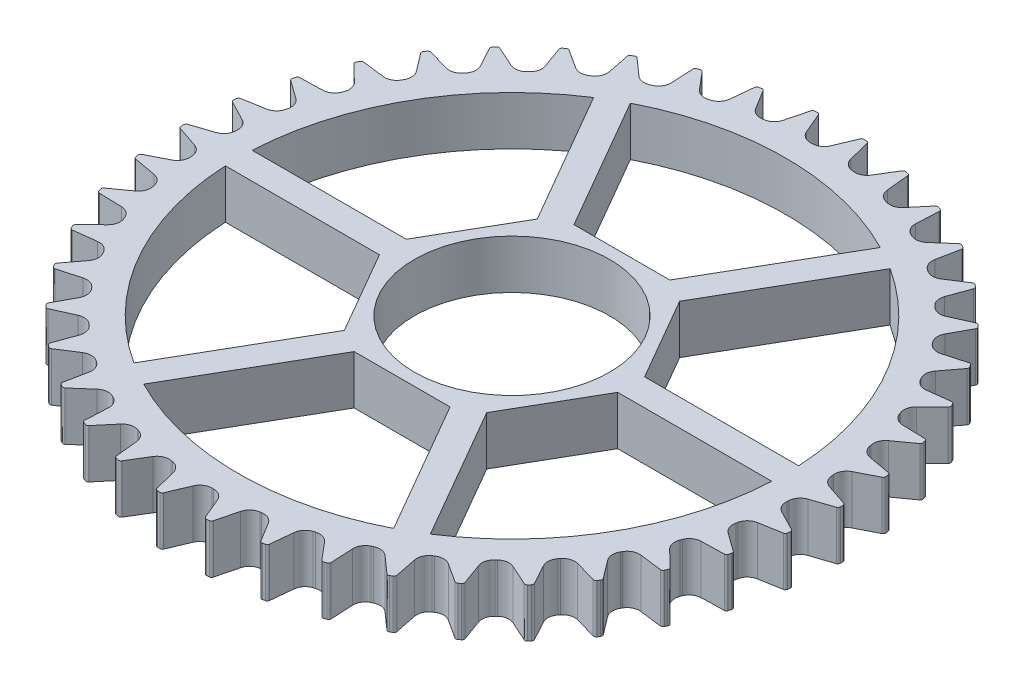
SolidWorks part; units mm, degrees
ref_plane "前视基准面" through (0, 0, 0) normal (0, 0, 1) x (1, 0, 0)
ref_plane "上视基准面" through (0, 0, 0) normal (0, 1, 0) x (1, 0, 0)
ref_plane "右视基准面" through (0, 0, 0) normal (1, 0, 0) x (0, 0, -1)
other "Configuration Table"
sketch "草图1" plane through (0, 0, 0) normal (0, 1, 0) x (1, 0, 0)
  line L0 (0, 0) -> (7.9279, 0) construction
  line L1 (0, 0) -> (0, 4.4256) construction
  line L2 (12.5574, 0.4423) -> (13.4318, 0.1478)
  line L3 (12.5574, -0.4423) -> (13.4318, -0.1478)
  line L4 (12.3513, -2.3089) -> (13.2598, -2.148)
  line L5 (12.4831, -1.4342) -> (13.3038, -1.8558)
  line L6 (11.8692, -4.124) -> (12.7915, -4.1003)
  line L7 (12.1299, -3.2787) -> (12.8786, -3.8179)
  line L8 (11.122, -5.847) -> (12.0375, -5.961)
  line L9 (11.5058, -5.05) -> (12.1658, -5.6947)
  line L10 (10.1263, -7.4393) -> (11.0146, -7.6885)
  line L11 (10.6246, -6.7084) -> (11.1811, -7.4443)
  line L12 (8.9044, -8.8654) -> (9.7457, -9.2443)
  line L13 (9.5061, -8.217) -> (9.9467, -9.0276)
  line L14 (7.4836, -10.0936) -> (8.2591, -10.5936)
  line L15 (8.1752, -9.542) -> (8.4901, -10.4093)
  line L16 (5.8957, -11.0962) -> (6.5879, -11.7062)
  line L17 (6.6618, -10.6539) -> (6.8439, -11.5584)
  line L18 (4.176, -11.851) -> (4.7696, -12.5573)
  line L19 (4.9995, -11.5278) -> (5.0447, -12.4493)
  line L20 (2.3631, -12.341) -> (2.8448, -13.1279)
  line L21 (3.2255, -12.1442) -> (3.1329, -13.0622)
  line L22 (0.4974, -12.5554) -> (0.8564, -13.4053)
  line L23 (1.3795, -12.4893) -> (1.1511, -13.3832)
  line L24 (-1.3795, -12.4893) -> (-1.1511, -13.3832)
  line L25 (-0.4974, -12.5554) -> (-0.8564, -13.4053)
  line L26 (-3.2255, -12.1442) -> (-3.1329, -13.0622)
  line L27 (-2.3631, -12.341) -> (-2.8448, -13.1279)
  line L28 (-4.9995, -11.5278) -> (-5.0447, -12.4493)
  line L29 (-4.176, -11.851) -> (-4.7696, -12.5573)
  line L30 (-6.6618, -10.6539) -> (-6.8439, -11.5584)
  line L31 (-5.8957, -11.0962) -> (-6.5879, -11.7062)
  line L32 (-8.1752, -9.542) -> (-8.4901, -10.4093)
  line L33 (-7.4836, -10.0936) -> (-8.2591, -10.5936)
  line L34 (-9.5061, -8.217) -> (-9.9467, -9.0276)
  line L35 (-8.9044, -8.8654) -> (-9.7457, -9.2443)
  line L36 (-10.6246, -6.7084) -> (-11.1811, -7.4443)
  line L37 (-10.1263, -7.4393) -> (-11.0146, -7.6885)
  line L38 (-11.5058, -5.05) -> (-12.1658, -5.6947)
  line L39 (-11.122, -5.847) -> (-12.0375, -5.961)
  line L40 (-12.1299, -3.2787) -> (-12.8786, -3.8179)
  line L41 (-11.8692, -4.124) -> (-12.7915, -4.1003)
  line L42 (-12.4831, -1.4342) -> (-13.3038, -1.8558)
  line L43 (-12.3513, -2.3089) -> (-13.2598, -2.148)
  line L44 (-12.5574, 0.4423) -> (-13.4318, 0.1478)
  line L45 (-12.5574, -0.4423) -> (-13.4318, -0.1478)
  line L46 (-12.3513, 2.3089) -> (-13.2598, 2.148)
  line L47 (-12.4831, 1.4342) -> (-13.3038, 1.8558)
  line L48 (-11.8692, 4.124) -> (-12.7915, 4.1003)
  line L49 (-12.1299, 3.2787) -> (-12.8786, 3.8179)
  line L50 (-11.122, 5.847) -> (-12.0375, 5.961)
  line L51 (-11.5058, 5.05) -> (-12.1658, 5.6947)
  line L52 (-10.1263, 7.4393) -> (-11.0146, 7.6885)
  line L53 (-10.6246, 6.7084) -> (-11.1811, 7.4443)
  line L54 (-8.9044, 8.8654) -> (-9.7457, 9.2443)
  line L55 (-9.5061, 8.217) -> (-9.9467, 9.0276)
  line L56 (-7.4836, 10.0936) -> (-8.2591, 10.5936)
  line L57 (-8.1752, 9.542) -> (-8.4901, 10.4093)
  line L58 (-5.8957, 11.0962) -> (-6.5879, 11.7062)
  line L59 (-6.6618, 10.6539) -> (-6.8439, 11.5584)
  line L60 (-4.176, 11.851) -> (-4.7696, 12.5573)
  line L61 (-4.9995, 11.5278) -> (-5.0447, 12.4493)
  line L62 (-2.3631, 12.341) -> (-2.8448, 13.1279)
  line L63 (-3.2255, 12.1442) -> (-3.1329, 13.0622)
  line L64 (-0.4974, 12.5554) -> (-0.8564, 13.4053)
  line L65 (-1.3795, 12.4893) -> (-1.1511, 13.3832)
  line L66 (1.3795, 12.4893) -> (1.1511, 13.3832)
  line L67 (0.4974, 12.5554) -> (0.8564, 13.4053)
  line L68 (3.2255, 12.1442) -> (3.1329, 13.0622)
  line L69 (2.3631, 12.341) -> (2.8448, 13.1279)
  line L70 (4.9995, 11.5278) -> (5.0447, 12.4493)
  line L71 (4.176, 11.851) -> (4.7696, 12.5573)
  line L72 (6.6618, 10.6539) -> (6.8439, 11.5584)
  line L73 (5.8957, 11.0962) -> (6.5879, 11.7062)
  line L74 (8.1752, 9.542) -> (8.4901, 10.4093)
  line L75 (7.4836, 10.0936) -> (8.2591, 10.5936)
  line L76 (9.5061, 8.217) -> (9.9467, 9.0276)
  line L77 (8.9044, 8.8654) -> (9.7457, 9.2443)
  line L78 (10.6246, 6.7084) -> (11.1811, 7.4443)
  line L79 (10.1263, 7.4393) -> (11.0146, 7.6885)
  line L80 (11.5058, 5.05) -> (12.1658, 5.6947)
  line L81 (11.122, 5.847) -> (12.0375, 5.961)
  line L82 (12.1299, 3.2787) -> (12.8786, 3.8179)
  line L83 (11.8692, 4.124) -> (12.7915, 4.1003)
  line L84 (12.4831, 1.4342) -> (13.3038, 1.8558)
  line L85 (12.3513, 2.3089) -> (13.2598, 2.148)
  line L95 (2.5981, 4.5) -> (-2.5981, 4.5) construction
  line L96 (2.5981, 4.5) -> (4.8786, 0.55) construction
  line L97 (0, 0) -> (2.5981, 4.5) construction
  line L98 (-2.5981, 4.5) -> (-4.8786, 0.55) construction
  line L99 (2.9156, -3.95) -> (4.8786, -0.55)
  line L100 (1.963, -4.5) -> (-1.963, -4.5)
  line L101 (-2.9156, -3.95) -> (-4.8786, -0.55)
  line L102 (8.1752, 0) -> (11.2, 0) construction
  line L103 (4.8786, 0.55) -> (11.1865, 0.55)
  line L104 (4.8786, -0.55) -> (11.1865, -0.55)
  line L105 (2.9156, -3.95) -> (6.0696, -9.4128)
  line L106 (1.963, -4.5) -> (5.1169, -9.9628)
  line L107 (-1.963, -4.5) -> (-5.1169, -9.9628)
  line L108 (-2.9156, -3.95) -> (-6.0696, -9.4128)
  line L109 (-4.8786, -0.55) -> (-11.1865, -0.55)
  line L110 (-4.8786, 0.55) -> (-11.1865, 0.55)
  line L111 (-2.9156, 3.95) -> (-6.0696, 9.4128)
  line L112 (-1.963, 4.5) -> (-5.1169, 9.9628)
  line L113 (1.963, 4.5) -> (5.1169, 9.9628)
  line L114 (2.9156, 3.95) -> (6.0696, 9.4128)
  line L115 (0, 0) -> (12.1829, 1.2805) construction
  line L116 (12.1829, -1.2805) -> (0, 0) construction
  line L117 (-4.8786, 0.55) -> (-2.9156, 3.95)
  line L118 (-1.963, 4.5) -> (1.963, 4.5)
  line L119 (2.9156, 3.95) -> (4.8786, 0.55)
  circle A0 centre (0, 0) radius 11.2 construction
  circle A1 centre (0, 0) radius 12.25 construction
  circle A2 centre (0, 0) radius 13.5 construction
  arc A3 (13.4999, 0.0534) -> (13.4999, -0.0534) centre (0, 0) cw
  arc A4 (12.2183, 0.8802) -> (12.1829, 1.2805) centre (0, 0) ccw construction
  arc A5 (13.4318, -0.1478) -> (13.4999, -0.0534) centre (13.3999, -0.053) ccw
  arc A6 (13.4318, 0.1478) -> (13.4999, 0.0534) centre (13.3999, 0.053) cw
  arc A7 (12.2183, -0.8802) -> (12.1829, -1.2805) centre (0, 0) cw construction
  arc A8 (12.5574, -0.4423) -> (12.2183, -0.8802) centre (12.717, -0.9161) ccw
  arc A9 (12.5574, 0.4423) -> (12.2183, 0.8802) centre (12.717, 0.9161) cw
  arc A10 (12.3513, -2.3089) -> (11.9507, -2.6914) centre (12.4385, -2.8013) ccw
  arc A11 (12.4831, -1.4342) -> (12.2131, -0.9507) centre (12.7115, -0.9895) cw
  arc A12 (13.3038, -1.8558) -> (13.3571, -1.9593) centre (13.2581, -1.9447) cw
  arc A13 (13.3571, -1.9593) -> (13.3412, -2.0649) centre (0, 0) cw
  arc A14 (13.2598, -2.148) -> (13.3412, -2.0649) centre (13.2423, -2.0496) ccw
  arc A15 (11.8692, -4.124) -> (11.4161, -4.4425) centre (11.882, -4.6238) ccw
  arc A16 (12.1299, -3.2787) -> (11.935, -2.7603) centre (12.4221, -2.873) cw
  arc A17 (12.8786, -3.8179) -> (12.9159, -3.9281) centre (12.8202, -3.899) cw
  arc A18 (12.9159, -3.9281) -> (12.8844, -4.0302) centre (0, 0) cw
  arc A19 (12.7915, -4.1003) -> (12.8844, -4.0302) centre (12.789, -4.0003) ccw
  arc A20 (11.122, -5.847) -> (10.6264, -6.0944) centre (11.0602, -6.3431) ccw
  arc A21 (11.5058, -5.05) -> (11.3902, -4.5083) centre (11.8552, -4.6923) cw
  arc A22 (12.1658, -5.6947) -> (12.1862, -5.8093) centre (12.0959, -5.7662) cw
  arc A23 (12.1862, -5.8093) -> (12.1398, -5.9055) centre (0, 0) cw
  arc A24 (12.0375, -5.961) -> (12.1398, -5.9055) centre (12.0499, -5.8618) ccw
  arc A25 (10.1263, -7.4393) -> (9.5994, -7.6101) centre (9.9912, -7.9207) ccw
  arc A26 (10.6246, -6.7084) -> (10.5911, -6.1556) centre (11.0234, -6.4068) cw
  arc A27 (11.1811, -7.4443) -> (11.1842, -7.5606) centre (11.1014, -7.5046) cw
  arc A28 (11.1842, -7.5606) -> (11.1241, -7.6489) centre (0, 0) cw
  arc A29 (11.0146, -7.6885) -> (11.1241, -7.6489) centre (11.0417, -7.5922) ccw
  arc A30 (8.9044, -8.8654) -> (8.358, -8.9558) centre (8.6991, -9.3214) ccw
  arc A31 (9.5061, -8.217) -> (9.5554, -7.6653) centre (9.9454, -7.9782) cw
  arc A32 (9.9467, -9.0276) -> (9.9324, -9.1431) centre (9.8589, -9.0754) cw
  arc A33 (9.9324, -9.1431) -> (9.8598, -9.2214) centre (0, 0) cw
  arc A34 (9.7457, -9.2443) -> (9.8598, -9.2214) centre (9.7868, -9.1531) ccw
  arc A35 (7.4836, -10.0936) -> (6.9298, -10.1015) centre (7.2127, -10.5138) ccw
  arc A36 (8.1752, -9.542) -> (8.3062, -9.0039) centre (8.6452, -9.3714) cw
  arc A37 (8.4901, -10.4093) -> (8.4588, -10.5213) centre (8.3961, -10.4434) cw
  arc A38 (8.4588, -10.5213) -> (8.3753, -10.5879) centre (0, 0) cw
  arc A39 (8.2591, -10.5936) -> (8.3753, -10.5879) centre (8.3133, -10.5095) ccw
  arc A40 (5.8957, -11.0962) -> (5.3469, -11.0215) centre (5.5651, -11.4713) ccw
  arc A41 (6.6618, -10.6539) -> (6.8714, -10.1413) centre (7.1519, -10.5552) cw
  arc A42 (6.8439, -11.5584) -> (6.7962, -11.6646) centre (6.7458, -11.5781) cw
  arc A43 (6.7962, -11.6646) -> (6.7037, -11.718) centre (0, 0) cw
  arc A44 (6.5879, -11.7062) -> (6.7037, -11.718) centre (6.654, -11.6312) ccw
  arc A45 (4.176, -11.851) -> (3.6445, -11.6953) centre (3.7933, -12.1727) ccw
  arc A46 (4.9995, -11.5278) -> (5.2832, -11.0522) centre (5.4989, -11.5033) cw
  arc A47 (5.0447, -12.4493) -> (4.9818, -12.5472) centre (4.9449, -12.4542) cw
  arc A48 (4.9818, -12.5472) -> (4.8824, -12.5862) centre (0, 0) cw
  arc A49 (4.7696, -12.5573) -> (4.8824, -12.5862) centre (4.8462, -12.493) ccw
  arc A50 (2.3631, -12.341) -> (1.8607, -12.1079) centre (1.9367, -12.6021) ccw
  arc A51 (3.2255, -12.1442) -> (3.577, -11.7161) centre (3.723, -12.1943) cw
  arc A52 (3.1329, -13.0622) -> (3.0561, -13.1495) centre (3.0334, -13.0521) cw
  arc A53 (3.0561, -13.1495) -> (2.9519, -13.1733) centre (0, 0) cw
  arc A54 (2.8448, -13.1279) -> (2.9519, -13.1733) centre (2.9301, -13.0757) ccw
  arc A55 (0.4974, -12.5554) -> (0.0353, -12.2499) centre (0.0368, -12.7499) ccw
  arc A56 (1.3795, -12.4893) -> (1.7908, -12.1184) centre (1.8639, -12.613) cw
  arc A57 (1.1511, -13.3832) -> (1.0621, -13.4582) centre (1.0542, -13.3585) cw
  arc A58 (1.0621, -13.4582) -> (0.9556, -13.4661) centre (0, 0) cw
  arc A59 (0.8564, -13.4053) -> (0.9556, -13.4661) centre (0.9485, -13.3664) ccw
  arc A60 (-1.3795, -12.4893) -> (-1.7908, -12.1184) centre (-1.8639, -12.613) ccw
  arc A61 (-0.4974, -12.5554) -> (-0.0353, -12.2499) centre (-0.0368, -12.7499) cw
  arc A62 (-0.8564, -13.4053) -> (-0.9556, -13.4661) centre (-0.9485, -13.3664) cw
  arc A63 (-0.9556, -13.4661) -> (-1.0621, -13.4582) centre (0, 0) cw
  arc A64 (-1.1511, -13.3832) -> (-1.0621, -13.4582) centre (-1.0542, -13.3585) ccw
  arc A65 (-3.2255, -12.1442) -> (-3.577, -11.7161) centre (-3.723, -12.1943) ccw
  arc A66 (-2.3631, -12.341) -> (-1.8607, -12.1079) centre (-1.9367, -12.6021) cw
  arc A67 (-2.8448, -13.1279) -> (-2.9519, -13.1733) centre (-2.9301, -13.0757) cw
  arc A68 (-2.9519, -13.1733) -> (-3.0561, -13.1495) centre (0, 0) cw
  arc A69 (-3.1329, -13.0622) -> (-3.0561, -13.1495) centre (-3.0334, -13.0521) ccw
  arc A70 (-4.9995, -11.5278) -> (-5.2832, -11.0522) centre (-5.4989, -11.5033) ccw
  arc A71 (-4.176, -11.851) -> (-3.6445, -11.6953) centre (-3.7933, -12.1727) cw
  arc A72 (-4.7696, -12.5573) -> (-4.8824, -12.5862) centre (-4.8462, -12.493) cw
  arc A73 (-4.8824, -12.5862) -> (-4.9818, -12.5472) centre (0, 0) cw
  arc A74 (-5.0447, -12.4493) -> (-4.9818, -12.5472) centre (-4.9449, -12.4542) ccw
  arc A75 (-6.6618, -10.6539) -> (-6.8714, -10.1413) centre (-7.1519, -10.5552) ccw
  arc A76 (-5.8957, -11.0962) -> (-5.3469, -11.0215) centre (-5.5651, -11.4713) cw
  arc A77 (-6.5879, -11.7062) -> (-6.7037, -11.718) centre (-6.654, -11.6312) cw
  arc A78 (-6.7037, -11.718) -> (-6.7962, -11.6646) centre (0, 0) cw
  arc A79 (-6.8439, -11.5584) -> (-6.7962, -11.6646) centre (-6.7458, -11.5781) ccw
  arc A80 (-8.1752, -9.542) -> (-8.3062, -9.0039) centre (-8.6452, -9.3714) ccw
  arc A81 (-7.4836, -10.0936) -> (-6.9298, -10.1015) centre (-7.2127, -10.5138) cw
  arc A82 (-8.2591, -10.5936) -> (-8.3753, -10.5879) centre (-8.3133, -10.5095) cw
  arc A83 (-8.3753, -10.5879) -> (-8.4588, -10.5213) centre (0, 0) cw
  arc A84 (-8.4901, -10.4093) -> (-8.4588, -10.5213) centre (-8.3961, -10.4434) ccw
  arc A85 (-9.5061, -8.217) -> (-9.5554, -7.6653) centre (-9.9454, -7.9782) ccw
  arc A86 (-8.9044, -8.8654) -> (-8.358, -8.9558) centre (-8.6991, -9.3214) cw
  arc A87 (-9.7457, -9.2443) -> (-9.8598, -9.2214) centre (-9.7868, -9.1531) cw
  arc A88 (-9.8598, -9.2214) -> (-9.9324, -9.1431) centre (0, 0) cw
  arc A89 (-9.9467, -9.0276) -> (-9.9324, -9.1431) centre (-9.8589, -9.0754) ccw
  arc A90 (-10.6246, -6.7084) -> (-10.5911, -6.1556) centre (-11.0234, -6.4068) ccw
  arc A91 (-10.1263, -7.4393) -> (-9.5994, -7.6101) centre (-9.9912, -7.9207) cw
  arc A92 (-11.0146, -7.6885) -> (-11.1241, -7.6489) centre (-11.0417, -7.5922) cw
  arc A93 (-11.1241, -7.6489) -> (-11.1842, -7.5606) centre (0, 0) cw
  arc A94 (-11.1811, -7.4443) -> (-11.1842, -7.5606) centre (-11.1014, -7.5046) ccw
  arc A95 (-11.5058, -5.05) -> (-11.3902, -4.5083) centre (-11.8552, -4.6923) ccw
  arc A96 (-11.122, -5.847) -> (-10.6264, -6.0944) centre (-11.0602, -6.3431) cw
  arc A97 (-12.0375, -5.961) -> (-12.1398, -5.9055) centre (-12.0499, -5.8618) cw
  arc A98 (-12.1398, -5.9055) -> (-12.1862, -5.8093) centre (0, 0) cw
  arc A99 (-12.1658, -5.6947) -> (-12.1862, -5.8093) centre (-12.0959, -5.7662) ccw
  arc A100 (-12.1299, -3.2787) -> (-11.935, -2.7603) centre (-12.4221, -2.873) ccw
  arc A101 (-11.8692, -4.124) -> (-11.4161, -4.4425) centre (-11.882, -4.6238) cw
  arc A102 (-12.7915, -4.1003) -> (-12.8844, -4.0302) centre (-12.789, -4.0003) cw
  arc A103 (-12.8844, -4.0302) -> (-12.9159, -3.9281) centre (0, 0) cw
  arc A104 (-12.8786, -3.8179) -> (-12.9159, -3.9281) centre (-12.8202, -3.899) ccw
  arc A105 (-12.4831, -1.4342) -> (-12.2131, -0.9507) centre (-12.7115, -0.9895) ccw
  arc A106 (-12.3513, -2.3089) -> (-11.9507, -2.6914) centre (-12.4385, -2.8013) cw
  arc A107 (-13.2598, -2.148) -> (-13.3412, -2.0649) centre (-13.2423, -2.0496) cw
  arc A108 (-13.3412, -2.0649) -> (-13.3571, -1.9593) centre (0, 0) cw
  arc A109 (-13.3038, -1.8558) -> (-13.3571, -1.9593) centre (-13.2581, -1.9447) ccw
  arc A110 (-12.5574, 0.4423) -> (-12.2183, 0.8802) centre (-12.717, 0.9161) ccw
  arc A111 (-12.5574, -0.4423) -> (-12.2183, -0.8802) centre (-12.717, -0.9161) cw
  arc A112 (-13.4318, -0.1478) -> (-13.4999, -0.0534) centre (-13.3999, -0.053) cw
  arc A113 (-13.4999, -0.0534) -> (-13.4999, 0.0534) centre (0, 0) cw
  arc A114 (-13.4318, 0.1478) -> (-13.4999, 0.0534) centre (-13.3999, 0.053) ccw
  arc A115 (-12.3513, 2.3089) -> (-11.9507, 2.6914) centre (-12.4385, 2.8013) ccw
  arc A116 (-12.4831, 1.4342) -> (-12.2131, 0.9507) centre (-12.7115, 0.9895) cw
  arc A117 (-13.3038, 1.8558) -> (-13.3571, 1.9593) centre (-13.2581, 1.9447) cw
  arc A118 (-13.3571, 1.9593) -> (-13.3412, 2.0649) centre (0, 0) cw
  arc A119 (-13.2598, 2.148) -> (-13.3412, 2.0649) centre (-13.2423, 2.0496) ccw
  arc A120 (-11.8692, 4.124) -> (-11.4161, 4.4425) centre (-11.882, 4.6238) ccw
  arc A121 (-12.1299, 3.2787) -> (-11.935, 2.7603) centre (-12.4221, 2.873) cw
  arc A122 (-12.8786, 3.8179) -> (-12.9159, 3.9281) centre (-12.8202, 3.899) cw
  arc A123 (-12.9159, 3.9281) -> (-12.8844, 4.0302) centre (0, 0) cw
  arc A124 (-12.7915, 4.1003) -> (-12.8844, 4.0302) centre (-12.789, 4.0003) ccw
  arc A125 (-11.122, 5.847) -> (-10.6264, 6.0944) centre (-11.0602, 6.3431) ccw
  arc A126 (-11.5058, 5.05) -> (-11.3902, 4.5083) centre (-11.8552, 4.6923) cw
  arc A127 (-12.1658, 5.6947) -> (-12.1862, 5.8093) centre (-12.0959, 5.7662) cw
  arc A128 (-12.1862, 5.8093) -> (-12.1398, 5.9055) centre (0, 0) cw
  arc A129 (-12.0375, 5.961) -> (-12.1398, 5.9055) centre (-12.0499, 5.8618) ccw
  arc A130 (-10.1263, 7.4393) -> (-9.5994, 7.6101) centre (-9.9912, 7.9207) ccw
  arc A131 (-10.6246, 6.7084) -> (-10.5911, 6.1556) centre (-11.0234, 6.4068) cw
  arc A132 (-11.1811, 7.4443) -> (-11.1842, 7.5606) centre (-11.1014, 7.5046) cw
  arc A133 (-11.1842, 7.5606) -> (-11.1241, 7.6489) centre (0, 0) cw
  arc A134 (-11.0146, 7.6885) -> (-11.1241, 7.6489) centre (-11.0417, 7.5922) ccw
  arc A135 (-8.9044, 8.8654) -> (-8.358, 8.9558) centre (-8.6991, 9.3214) ccw
  arc A136 (-9.5061, 8.217) -> (-9.5554, 7.6653) centre (-9.9454, 7.9782) cw
  arc A137 (-9.9467, 9.0276) -> (-9.9324, 9.1431) centre (-9.8589, 9.0754) cw
  arc A138 (-9.9324, 9.1431) -> (-9.8598, 9.2214) centre (0, 0) cw
  arc A139 (-9.7457, 9.2443) -> (-9.8598, 9.2214) centre (-9.7868, 9.1531) ccw
  arc A140 (-7.4836, 10.0936) -> (-6.9298, 10.1015) centre (-7.2127, 10.5138) ccw
  arc A141 (-8.1752, 9.542) -> (-8.3062, 9.0039) centre (-8.6452, 9.3714) cw
  arc A142 (-8.4901, 10.4093) -> (-8.4588, 10.5213) centre (-8.3961, 10.4434) cw
  arc A143 (-8.4588, 10.5213) -> (-8.3753, 10.5879) centre (0, 0) cw
  arc A144 (-8.2591, 10.5936) -> (-8.3753, 10.5879) centre (-8.3133, 10.5095) ccw
  arc A145 (-5.8957, 11.0962) -> (-5.3469, 11.0215) centre (-5.5651, 11.4713) ccw
  arc A146 (-6.6618, 10.6539) -> (-6.8714, 10.1413) centre (-7.1519, 10.5552) cw
  arc A147 (-6.8439, 11.5584) -> (-6.7962, 11.6646) centre (-6.7458, 11.5781) cw
  arc A148 (-6.7962, 11.6646) -> (-6.7037, 11.718) centre (0, 0) cw
  arc A149 (-6.5879, 11.7062) -> (-6.7037, 11.718) centre (-6.654, 11.6312) ccw
  arc A150 (-4.176, 11.851) -> (-3.6445, 11.6953) centre (-3.7933, 12.1727) ccw
  arc A151 (-4.9995, 11.5278) -> (-5.2832, 11.0522) centre (-5.4989, 11.5033) cw
  arc A152 (-5.0447, 12.4493) -> (-4.9818, 12.5472) centre (-4.9449, 12.4542) cw
  arc A153 (-4.9818, 12.5472) -> (-4.8824, 12.5862) centre (0, 0) cw
  arc A154 (-4.7696, 12.5573) -> (-4.8824, 12.5862) centre (-4.8462, 12.493) ccw
  arc A155 (-2.3631, 12.341) -> (-1.8607, 12.1079) centre (-1.9367, 12.6021) ccw
  arc A156 (-3.2255, 12.1442) -> (-3.577, 11.7161) centre (-3.723, 12.1943) cw
  arc A157 (-3.1329, 13.0622) -> (-3.0561, 13.1495) centre (-3.0334, 13.0521) cw
  arc A158 (-3.0561, 13.1495) -> (-2.9519, 13.1733) centre (0, 0) cw
  arc A159 (-2.8448, 13.1279) -> (-2.9519, 13.1733) centre (-2.9301, 13.0757) ccw
  arc A160 (-0.4974, 12.5554) -> (-0.0353, 12.2499) centre (-0.0368, 12.7499) ccw
  arc A161 (-1.3795, 12.4893) -> (-1.7908, 12.1184) centre (-1.8639, 12.613) cw
  arc A162 (-1.1511, 13.3832) -> (-1.0621, 13.4582) centre (-1.0542, 13.3585) cw
  arc A163 (-1.0621, 13.4582) -> (-0.9556, 13.4661) centre (0, 0) cw
  arc A164 (-0.8564, 13.4053) -> (-0.9556, 13.4661) centre (-0.9485, 13.3664) ccw
  arc A165 (1.3795, 12.4893) -> (1.7908, 12.1184) centre (1.8639, 12.613) ccw
  arc A166 (0.4974, 12.5554) -> (0.0353, 12.2499) centre (0.0368, 12.7499) cw
  arc A167 (0.8564, 13.4053) -> (0.9556, 13.4661) centre (0.9485, 13.3664) cw
  arc A168 (0.9556, 13.4661) -> (1.0621, 13.4582) centre (0, 0) cw
  arc A169 (1.1511, 13.3832) -> (1.0621, 13.4582) centre (1.0542, 13.3585) ccw
  arc A170 (3.2255, 12.1442) -> (3.577, 11.7161) centre (3.723, 12.1943) ccw
  arc A171 (2.3631, 12.341) -> (1.8607, 12.1079) centre (1.9367, 12.6021) cw
  arc A172 (2.8448, 13.1279) -> (2.9519, 13.1733) centre (2.9301, 13.0757) cw
  arc A173 (2.9519, 13.1733) -> (3.0561, 13.1495) centre (0, 0) cw
  arc A174 (3.1329, 13.0622) -> (3.0561, 13.1495) centre (3.0334, 13.0521) ccw
  arc A175 (4.9995, 11.5278) -> (5.2832, 11.0522) centre (5.4989, 11.5033) ccw
  arc A176 (4.176, 11.851) -> (3.6445, 11.6953) centre (3.7933, 12.1727) cw
  arc A177 (4.7696, 12.5573) -> (4.8824, 12.5862) centre (4.8462, 12.493) cw
  arc A178 (4.8824, 12.5862) -> (4.9818, 12.5472) centre (0, 0) cw
  arc A179 (5.0447, 12.4493) -> (4.9818, 12.5472) centre (4.9449, 12.4542) ccw
  arc A180 (6.6618, 10.6539) -> (6.8714, 10.1413) centre (7.1519, 10.5552) ccw
  arc A181 (5.8957, 11.0962) -> (5.3469, 11.0215) centre (5.5651, 11.4713) cw
  arc A182 (6.5879, 11.7062) -> (6.7037, 11.718) centre (6.654, 11.6312) cw
  arc A183 (6.7037, 11.718) -> (6.7962, 11.6646) centre (0, 0) cw
  arc A184 (6.8439, 11.5584) -> (6.7962, 11.6646) centre (6.7458, 11.5781) ccw
  arc A185 (8.1752, 9.542) -> (8.3062, 9.0039) centre (8.6452, 9.3714) ccw
  arc A186 (7.4836, 10.0936) -> (6.9298, 10.1015) centre (7.2127, 10.5138) cw
  arc A187 (8.2591, 10.5936) -> (8.3753, 10.5879) centre (8.3133, 10.5095) cw
  arc A188 (8.3753, 10.5879) -> (8.4588, 10.5213) centre (0, 0) cw
  arc A189 (8.4901, 10.4093) -> (8.4588, 10.5213) centre (8.3961, 10.4434) ccw
  arc A190 (9.5061, 8.217) -> (9.5554, 7.6653) centre (9.9454, 7.9782) ccw
  arc A191 (8.9044, 8.8654) -> (8.358, 8.9558) centre (8.6991, 9.3214) cw
  arc A192 (9.7457, 9.2443) -> (9.8598, 9.2214) centre (9.7868, 9.1531) cw
  arc A193 (9.8598, 9.2214) -> (9.9324, 9.1431) centre (0, 0) cw
  arc A194 (9.9467, 9.0276) -> (9.9324, 9.1431) centre (9.8589, 9.0754) ccw
  arc A195 (10.6246, 6.7084) -> (10.5911, 6.1556) centre (11.0234, 6.4068) ccw
  arc A196 (10.1263, 7.4393) -> (9.5994, 7.6101) centre (9.9912, 7.9207) cw
  arc A197 (11.0146, 7.6885) -> (11.1241, 7.6489) centre (11.0417, 7.5922) cw
  arc A198 (11.1241, 7.6489) -> (11.1842, 7.5606) centre (0, 0) cw
  arc A199 (11.1811, 7.4443) -> (11.1842, 7.5606) centre (11.1014, 7.5046) ccw
  arc A200 (11.5058, 5.05) -> (11.3902, 4.5083) centre (11.8552, 4.6923) ccw
  arc A201 (11.122, 5.847) -> (10.6264, 6.0944) centre (11.0602, 6.3431) cw
  arc A202 (12.0375, 5.961) -> (12.1398, 5.9055) centre (12.0499, 5.8618) cw
  arc A203 (12.1398, 5.9055) -> (12.1862, 5.8093) centre (0, 0) cw
  arc A204 (12.1658, 5.6947) -> (12.1862, 5.8093) centre (12.0959, 5.7662) ccw
  arc A205 (12.1299, 3.2787) -> (11.935, 2.7603) centre (12.4221, 2.873) ccw
  arc A206 (11.8692, 4.124) -> (11.4161, 4.4425) centre (11.882, 4.6238) cw
  arc A207 (12.7915, 4.1003) -> (12.8844, 4.0302) centre (12.789, 4.0003) cw
  arc A208 (12.8844, 4.0302) -> (12.9159, 3.9281) centre (0, 0) cw
  arc A209 (12.8786, 3.8179) -> (12.9159, 3.9281) centre (12.8202, 3.899) ccw
  arc A210 (12.4831, 1.4342) -> (12.2131, 0.9507) centre (12.7115, 0.9895) ccw
  arc A211 (12.3513, 2.3089) -> (11.9507, 2.6914) centre (12.4385, 2.8013) cw
  arc A212 (13.2598, 2.148) -> (13.3412, 2.0649) centre (13.2423, 2.0496) cw
  arc A213 (13.3412, 2.0649) -> (13.3571, 1.9593) centre (0, 0) cw
  arc A214 (13.3038, 1.8558) -> (13.3571, 1.9593) centre (13.2581, 1.9447) ccw
  circle A216 centre (0, 0) radius 4
  arc A217 (11.1865, 0.55) -> (6.0696, 9.4128) centre (0, 0) ccw
  arc A218 (5.1169, 9.9628) -> (-5.1169, 9.9628) centre (0, 0) ccw
  arc A219 (-6.0696, 9.4128) -> (-11.1865, 0.55) centre (0, 0) ccw
  arc A220 (-11.1865, -0.55) -> (-6.0696, -9.4128) centre (0, 0) ccw
  arc A221 (-5.1169, -9.9628) -> (5.1169, -9.9628) centre (0, 0) ccw
  arc A222 (6.0696, -9.4128) -> (11.1865, -0.55) centre (0, 0) ccw
  arc A223 (12.2131, 0.9507) -> (12.2183, 0.8802) centre (0, 0) cw
  arc A224 (12.2183, -0.8802) -> (12.2131, -0.9507) centre (0, 0) cw
  arc A225 (11.9507, -2.6914) -> (11.935, -2.7603) centre (0, 0) cw
  arc A226 (11.4161, -4.4425) -> (11.3902, -4.5083) centre (0, 0) cw
  arc A227 (10.6264, -6.0944) -> (10.5911, -6.1556) centre (0, 0) cw
  arc A228 (9.5994, -7.6101) -> (9.5554, -7.6653) centre (0, 0) cw
  arc A229 (8.358, -8.9558) -> (8.3062, -9.0039) centre (0, 0) cw
  arc A230 (6.9298, -10.1015) -> (6.8714, -10.1413) centre (0, 0) cw
  arc A231 (5.3469, -11.0215) -> (5.2832, -11.0522) centre (0, 0) cw
  arc A232 (3.6445, -11.6953) -> (3.577, -11.7161) centre (0, 0) cw
  arc A233 (1.8607, -12.1079) -> (1.7908, -12.1184) centre (0, 0) cw
  arc A234 (0.0353, -12.2499) -> (-0.0353, -12.2499) centre (0, 0) cw
  arc A235 (-1.7908, -12.1184) -> (-1.8607, -12.1079) centre (0, 0) cw
  arc A236 (-3.577, -11.7161) -> (-3.6445, -11.6953) centre (0, 0) cw
  arc A237 (-5.2832, -11.0522) -> (-5.3469, -11.0215) centre (0, 0) cw
  arc A238 (-6.8714, -10.1413) -> (-6.9298, -10.1015) centre (0, 0) cw
  arc A239 (-8.3062, -9.0039) -> (-8.358, -8.9558) centre (0, 0) cw
  arc A240 (-9.5554, -7.6653) -> (-9.5994, -7.6101) centre (0, 0) cw
  arc A241 (-10.5911, -6.1556) -> (-10.6264, -6.0944) centre (0, 0) cw
  arc A242 (-11.3902, -4.5083) -> (-11.4161, -4.4425) centre (0, 0) cw
  arc A243 (-11.935, -2.7603) -> (-11.9507, -2.6914) centre (0, 0) cw
  arc A244 (-12.2131, -0.9507) -> (-12.2183, -0.8802) centre (0, 0) cw
  arc A245 (-12.2183, 0.8802) -> (-12.2131, 0.9507) centre (0, 0) cw
  arc A246 (-11.9507, 2.6914) -> (-11.935, 2.7603) centre (0, 0) cw
  arc A247 (-11.4161, 4.4425) -> (-11.3902, 4.5083) centre (0, 0) cw
  arc A248 (-10.6264, 6.0944) -> (-10.5911, 6.1556) centre (0, 0) cw
  arc A249 (-9.5994, 7.6101) -> (-9.5554, 7.6653) centre (0, 0) cw
  arc A250 (-8.358, 8.9558) -> (-8.3062, 9.0039) centre (0, 0) cw
  arc A251 (-6.9298, 10.1015) -> (-6.8714, 10.1413) centre (0, 0) cw
  arc A252 (-5.3469, 11.0215) -> (-5.2832, 11.0522) centre (0, 0) cw
  arc A253 (-3.6445, 11.6953) -> (-3.577, 11.7161) centre (0, 0) cw
  arc A254 (-1.8607, 12.1079) -> (-1.7908, 12.1184) centre (0, 0) cw
  arc A255 (-0.0353, 12.2499) -> (0.0353, 12.2499) centre (0, 0) cw
  arc A256 (1.7908, 12.1184) -> (1.8607, 12.1079) centre (0, 0) cw
  arc A257 (3.577, 11.7161) -> (3.6445, 11.6953) centre (0, 0) cw
  arc A258 (5.2832, 11.0522) -> (5.3469, 11.0215) centre (0, 0) cw
  arc A259 (6.8714, 10.1413) -> (6.9298, 10.1015) centre (0, 0) cw
  arc A260 (8.3062, 9.0039) -> (8.358, 8.9558) centre (0, 0) cw
  arc A261 (9.5554, 7.6653) -> (9.5994, 7.6101) centre (0, 0) cw
  arc A262 (10.5911, 6.1556) -> (10.6264, 6.0944) centre (0, 0) cw
  arc A263 (11.3902, 4.5083) -> (11.4161, 4.4425) centre (0, 0) cw
  arc A264 (11.935, 2.7603) -> (11.9507, 2.6914) centre (0, 0) cw
  point P17 (13.4994, -0.125)
  point P20 (13.4994, 0.125)
  point P23 (12.2376, -0.55)
  point P26 (12.2376, 0.55)
  point P524 (0, 4.5)
  dimension "D1" = 22.4
  dimension "D2" = 24.5
  dimension "D3" = 27
  dimension "D6" = 0.1
  dimension "D7" = 0.5
  dimension "D9" = 120
  dimension "D12" = 8
  dimension "D4" = 1.1
  dimension "D5" = 0.25
  dimension "D10" = 4.5
  dimension "D11" = 30
  dimension "D14" = 1.1
  dimension "D16" = 6
  dimension "D17" = 6
  dimension "D8" = 42
  dimension "D13" = 6
  dimension "D15" = 42
extrude "凸台-拉伸1" add sketch "草图1" along normal blind 2
